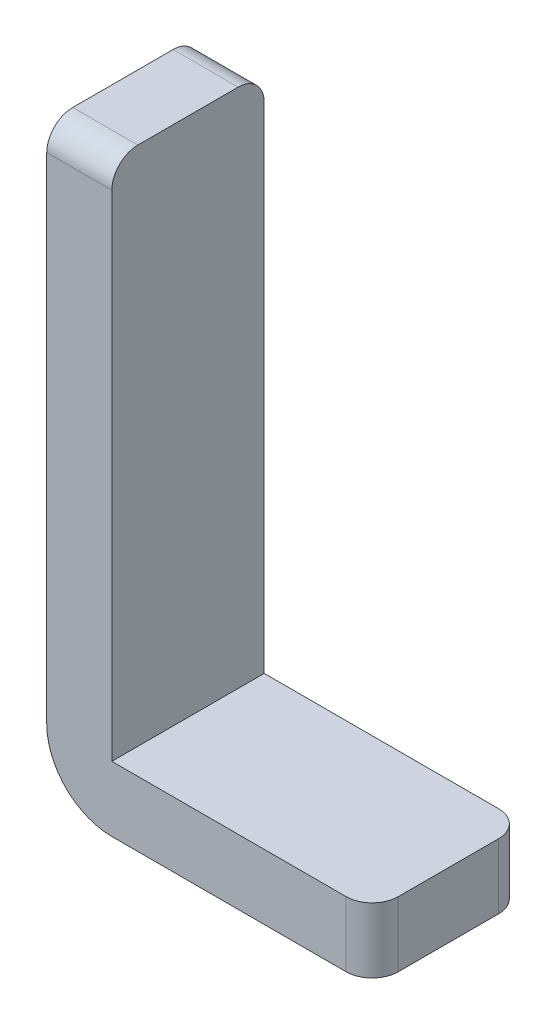
SolidWorks part; units mm, degrees
ref_plane "Front Plane" through (0, 0, 0) normal (0, 0, 1) x (1, 0, 0)
ref_plane "Top Plane" through (0, 0, 0) normal (0, 1, 0) x (1, 0, 0)
ref_plane "Right Plane" through (0, 0, 0) normal (1, 0, 0) x (0, 0, -1)
sketch "Sketch1" plane through (0, 0, 0) normal (0, 1, 0) x (1, 0, 0)
  line L0 (0, 0) -> (25, 0)
  line L1 (25, 0) -> (25, 11.7041)
  line L2 (0, 11.7041) -> (0, 0)
  line L3 (0, 11.7041) -> (25, 11.7041)
extrude "Boss-Extrude1" add sketch "Sketch1" along normal blind 5
sketch "Sketch2" plane through (0, 5, 0) normal (0, 1, 0) x (1, 0, 0)
  line L0 (0, 11.7041) -> (5, 11.7041)
  line L1 (25, 11.7041) -> (0, 11.7041) construction
  line L2 (5, 11.7041) -> (5, 0)
  line L3 (0, 0) -> (25, 0) construction
  line L4 (5, 0) -> (0, 0)
  line L5 (0, 0) -> (0, 11.7041)
extrude "Boss-Extrude2" add sketch "Sketch2" along normal blind 40
fillet "Fillet1" radius 5 1 edges at (0, 0, -5.8521)
fillet "Fillet2" radius 2 4 edges at (2.5, 45, 0) (2.5, 45, -11.7041) (25, 2.5, -11.7041) (25, 2.5, 0)
